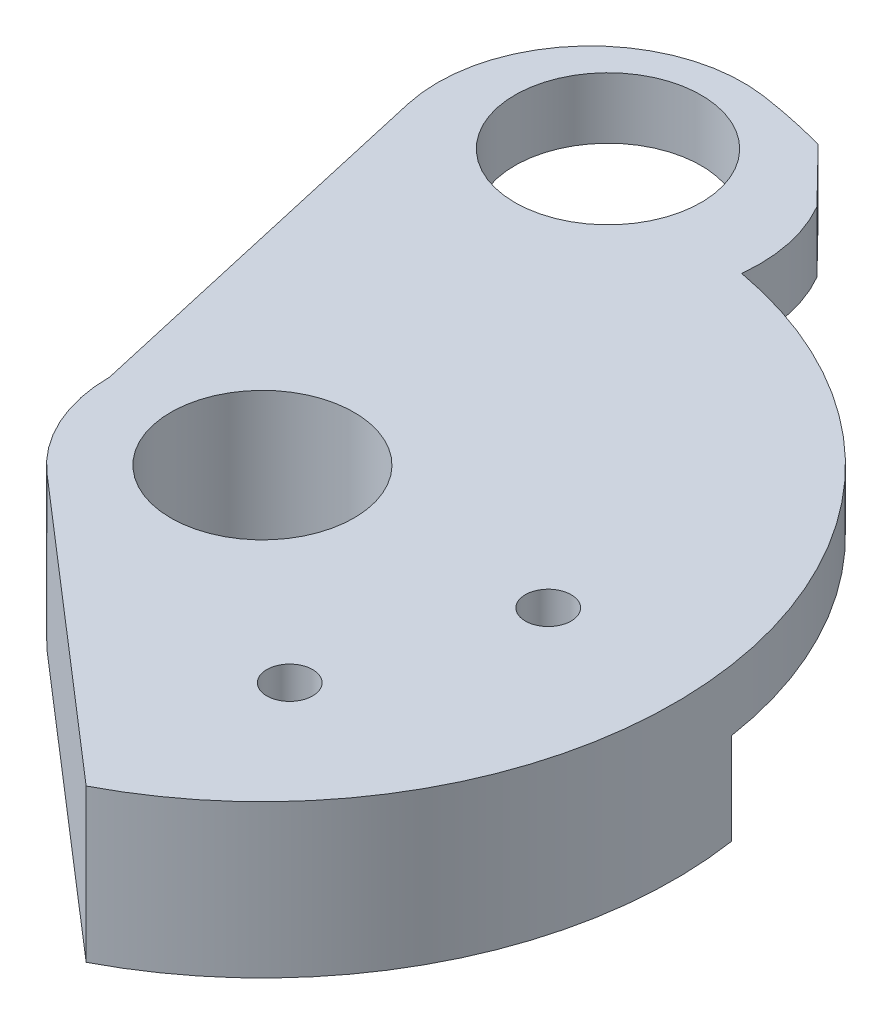
SolidWorks part; units mm, degrees
ref_plane "前视基准面" through (0, 0, 0) normal (0, 0, 1) x (1, 0, 0)
ref_plane "上视基准面" through (0, 0, 0) normal (0, 1, 0) x (1, 0, 0)
ref_plane "右视基准面" through (0, 0, 0) normal (1, 0, 0) x (0, 0, -1)
other "Configuration Table"
sketch "草图1" plane through (0, 0, 0) normal (0, 1, 0) x (1, 0, 0)
  line L0 (-23.091, 20.6857) -> (-17.3746, -4.5535)
  line L1 (-13.9167, -12.1165) -> (9.8679, -32.6906)
  line L2 (-3.8738, 28.2603) -> (-7.3746, 31.841)
  circle A0 centre (-7.3746, -4.5535) radius 6
  circle A1 centre (-14.0014, 24.7055) radius 6.1
  circle A2 centre (5.8608, -16.0022) radius 1.5
  circle A3 centre (10.0798, -3.2902) radius 1.5
  arc A4 (-7.3746, 31.841) -> (-11.883, 32.7882) centre (-17.3746, -4.5535) ccw
  arc A5 (-11.883, 32.7882) -> (-23.091, 20.6857) centre (-13.338, 22.8947) ccw
  arc A6 (-17.3746, -4.5535) -> (-13.9167, -12.1165) centre (-7.3746, -4.5535) ccw
  arc A7 (9.8679, -32.6906) -> (10.6418, -32.2015) centre (-7.3746, -4.5535) ccw
  arc A8 (10.6418, -32.2015) -> (8.9823, -26.0349) centre (0.3959, -31.6522) ccw
  arc A9 (8.9823, -26.0349) -> (11.2837, -24.0694) centre (-7.3746, -4.5535) ccw
  arc A10 (11.2837, -24.0694) -> (17.1147, -26.6731) centre (18.175, -16.4674) ccw
  arc A11 (17.1147, -26.6731) -> (18.3037, -25.2809) centre (-7.3746, -4.5535) ccw
  arc A12 (18.3037, -25.2809) -> (14.8199, -19.929) centre (8.3895, -27.9247) ccw
  arc A13 (14.8199, -19.929) -> (16.4012, -17.3485) centre (-7.3746, -4.5535) ccw
  arc A14 (16.4012, -17.3485) -> (22.7514, -18.0229) centre (20.6061, -7.989) ccw
  arc A15 (22.7514, -18.0229) -> (23.452, -16.3314) centre (-7.3746, -4.5535) ccw
  arc A16 (23.452, -16.3314) -> (18.4849, -12.318) centre (14.8401, -21.9094) ccw
  arc A17 (18.4849, -12.318) -> (19.1914, -9.3751) centre (-7.3746, -4.5535) ccw
  arc A18 (19.1914, -9.3751) -> (25.4392, -8.0542) centre (20.2983, 0.8256) ccw
  arc A19 (25.4392, -8.0542) -> (25.5829, -6.229) centre (-7.3746, -4.5535) ccw
  arc A20 (25.5829, -6.229) -> (19.6186, -3.947) centre (19.1161, -14.1953) ccw
  arc A21 (19.6186, -3.947) -> (19.3812, -0.9298) centre (-7.3746, -4.5535) ccw
  arc A22 (19.3812, -0.9298) -> (24.915, 2.2572) centre (17.2816, 9.1137) ccw
  arc A23 (24.915, 2.2572) -> (24.4876, 4.0374) centre (-7.3746, -4.5535) ccw
  arc A24 (24.4876, 4.0374) -> (18.1101, 4.3647) centre (20.799, -5.5373) ccw
  arc A25 (18.1101, 4.3647) -> (16.9519, 7.1608) centre (-7.3746, -4.5535) ccw
  arc A26 (16.9519, 7.1608) -> (21.23, 11.9019) centre (11.8515, 16.064) ccw
  arc A27 (21.23, 11.9019) -> (20.2734, 13.4629) centre (-7.3746, -4.5535) ccw
  arc A28 (20.2734, 13.4629) -> (14.1069, 11.8034) centre (19.7241, 3.217) ccw
  arc A29 (14.1069, 11.8034) -> (12.1413, 14.1048) centre (-7.3746, -4.5535) ccw
  arc A30 (12.1413, 14.1048) -> (14.745, 19.9358) centre (4.5394, 20.9961) ccw
  arc A31 (14.745, 19.9358) -> (13.3529, 21.1248) centre (-7.3746, -4.5535) ccw
  arc A32 (13.3529, 21.1248) -> (8.001, 17.641) centre (15.9966, 11.2106) ccw
  arc A33 (8.001, 17.641) -> (5.4205, 19.2223) centre (-7.3746, -4.5535) ccw
  arc A34 (5.4205, 19.2223) -> (6.0948, 25.5725) centre (-3.939, 23.4272) ccw
  arc A35 (6.0948, 25.5725) -> (4.4034, 26.2731) centre (-7.3746, -4.5535) ccw
  arc A36 (4.4034, 26.2731) -> (0.39, 21.306) centre (9.9814, 17.6612) ccw
  arc A37 (0.39, 21.306) -> (-2.5529, 22.0125) centre (-7.3746, -4.5535) ccw
  arc A38 (-2.5529, 22.0125) -> (-3.8738, 28.2603) centre (-12.7536, 23.1194) ccw
  circle A39 centre (-7.3746, -4.5535) radius 27
extrude "凸台-拉伸1" add sketch "草图1" along normal blind 4 contours A39 A38 L2 A4 A5 L0 A1 | L1 A39 A9 A13 A17 A21 A25 A29 A33 A37 A1 L0 A6 A0 A2 A3
sketch "草图2" plane through (0, 4, 0) normal (0, 1, 0) x (1, 0, 0)
  line L0 (-5.0942, 5.1831) -> (19.3249, -0.536)
  line L3 (-3.8738, 28.2603) -> (-7.3746, 31.841)
  line L4 (-23.091, 20.6857) -> (-17.3746, -4.5535)
  line L5 (-13.9167, -12.1165) -> (5.0513, -28.5242)
  line L6 (-3.8738, 28.2603) -> (-7.3746, 31.841)
  line L7 (-23.091, 20.6857) -> (-17.3746, -4.5535)
  line L8 (-13.9167, -12.1165) -> (5.0513, -28.5242)
  circle A0 centre (-7.3746, -4.5535) radius 6 construction
  circle A1 centre (-7.3746, -4.5535) radius 6
  circle A2 centre (-7.3746, -4.5535) radius 10
  arc A8 (5.0513, -28.5242) -> (-2.5529, 22.0125) centre (-7.3746, -4.5535) ccw
  arc A9 (-2.5529, 22.0125) -> (-3.8738, 28.2603) centre (-12.7536, 23.1194) ccw
  arc A10 (-7.3746, 31.841) -> (-11.883, 32.7882) centre (-17.3746, -4.5535) ccw
  arc A11 (-11.883, 32.7882) -> (-23.091, 20.6857) centre (-13.338, 22.8947) ccw
  arc A12 (-17.3746, -4.5535) -> (-13.9167, -12.1165) centre (-7.3746, -4.5535) ccw
  arc A13 (5.0513, -28.5242) -> (-2.5529, 22.0125) centre (-7.3746, -4.5535) ccw
  arc A14 (-2.5529, 22.0125) -> (-3.8738, 28.2603) centre (-12.7536, 23.1194) ccw
  arc A15 (-7.3746, 31.841) -> (-11.883, 32.7882) centre (-17.3746, -4.5535) ccw
  arc A16 (-11.883, 32.7882) -> (-23.091, 20.6857) centre (-13.338, 22.8947) ccw
  arc A17 (-17.3746, -4.5535) -> (-13.9167, -12.1165) centre (-7.3746, -4.5535) ccw
  point P12 (-3.1629, 4.5164)
  arc M2 (5.0513, -28.5242) -> (-2.5529, 22.0125) centre (-7.3746, -4.5535) ccw
  arc M8 (-17.3746, -4.5535) -> (-13.9167, -12.1165) centre (-7.3746, -4.5535) ccw
  line M9 (-13.9167, -12.1165) -> (5.0513, -28.5242)
  circle M10 centre (-7.3746, -4.5535) radius 6
  circle M11 centre (5.8608, -16.0022) radius 1.5
  circle M12 centre (10.0798, -3.2902) radius 1.5
  dimension "D1" = 0
extrude "凸台-拉伸3" add sketch "草图2" against normal blind 10 contours A2 M8 M10 | A2 L0 M9 M2 M11 M12
